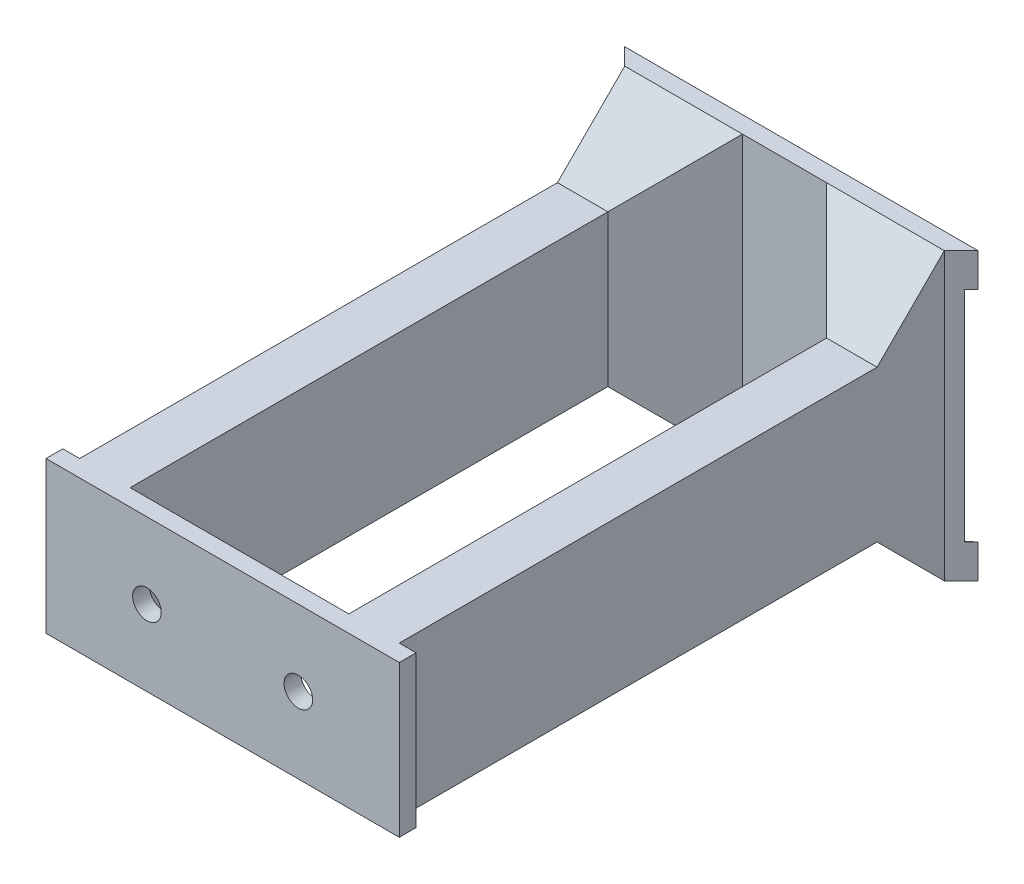
SolidWorks part; units mm, degrees
ref_plane "Front Plane" through (0, 0, 0) normal (0, 0, 1) x (1, 0, 0)
ref_plane "Top Plane" through (0, 0, 0) normal (0, 1, 0) x (1, 0, 0)
ref_plane "Right Plane" through (0, 0, 0) normal (1, 0, 0) x (0, 0, -1)
sketch "Sketch1" plane through (0, 0, 0) normal (0, 1, 0) x (1, 0, 0)
  line L0 (20, 5) -> (85, 5)
  line L2 (20, 5) -> (20, 167)
  line L3 (20, 167) -> (85, 167)
  line L4 (85, 5) -> (85, 167)
  line L5 (0, 0) -> (105, 0)
  line L6 (0, 0) -> (0, 5)
  line L7 (0, 5) -> (5, 5)
  line L8 (105, 0) -> (105, 5)
  line L9 (20, 5) -> (85, 5)
  line L10 (5, 5) -> (5, 167)
  line L11 (0, 172) -> (105, 172)
  line L12 (100, 5) -> (100, 167)
  line L13 (100, 5) -> (105, 5)
  line L14 (5, 167) -> (0, 172)
  line L16 (100, 167) -> (105, 172)
  point P13 (20, 86)
  dimension "D1" = 5
  dimension "D2" = 172
  dimension "D3" = 5
  dimension "D4" = 105
  dimension "D5" = 15
  dimension "D6" = 15
  dimension "D7" = 95
extrude "Boss-Extrude1" add sketch "Sketch1" along normal mid plane 85 contours L12 L16 L11 L14 L10 L7 L6 L5 L8 L13 L4 L0 L2 L3
sketch "Sketch2" plane through (0, 0, 0) normal (1, 0, 0) x (0, 0, -1)
  line L1 (0, -22.5) -> (0, 22.5) construction
  line L2 (0, 22.5) -> (147, 22.5)
  line L3 (147, 22.5) -> (167, 42.5)
  line L4 (167, 42.5) -> (0, 42.5)
  line L5 (0, 42.5) -> (0, 22.5)
  point P7 (0, 0)
  dimension "D1" = 45
  dimension "D2" = 45
extrude "Cut-Extrude1" cut sketch "Sketch2" along normal through all
mirror "Mirror1" about plane through (0, 0, 0) normal (0, 1, 0) of "Cut-Extrude1"
ref_plane "Plane1" through (0, 0, -170) normal (0, 0, -1) x (-1, 0, 0)
sketch "Sketch3" plane through (0, 0, -170) normal (0, 0, -1) x (-1, 0, 0)
  line L0 (0, 42.5) -> (0, -42.5) construction
  line L1 (-102.5, 40) -> (0, 40)
  line L2 (-102.5, 40) -> (-102.5, -40)
  line L3 (-102.5, -40) -> (0, -40)
  line L4 (0, 40) -> (0, -40)
  point P10 (0, 0)
  dimension "D1" = 80
  dimension "D2" = 102.5
loft "Cut-Loft1" cut profiles "Sketch3" section "Sketch3" section face at (52.5, 0, -172)
sketch "Sketch4" plane through (0, 0, 0) normal (0, 0, 1) x (1, 0, 0)
  line L0 (0, 0) -> (30, 0) construction
  line L1 (75, 0) -> (105, 0) construction
  line L2 (105, 22.5) -> (105, -22.5) construction
  circle A0 centre (30, 0) radius 4.25
  circle A1 centre (75, 0) radius 4.25
  dimension "D1" = 8.5
  dimension "D2" = 45
extrude "Cut-Extrude2" cut sketch "Sketch4" against normal up to next
sketch "Sketch5" plane through (0, 0, 0) normal (1, 0, 0) x (0, 0, -1)
  line L1 (170, 32.5) -> (172, 32.5)
  line L2 (170, 32.5) -> (170, -32.5)
  line L3 (170, -32.5) -> (172, -32.5)
  line L4 (172, 32.5) -> (172, -32.5)
  line L5 (172, 42.5) -> (172, -42.5) construction
  dimension "D1" = 10
  dimension "D2" = 10
  dimension "D3" = 2
extrude "Cut-Extrude3" cut sketch "Sketch5" along normal through all
chamfer "Chamfer1" distance 20 angle 45 2 edges at (85, 0, -167) (20, 0, -167)
